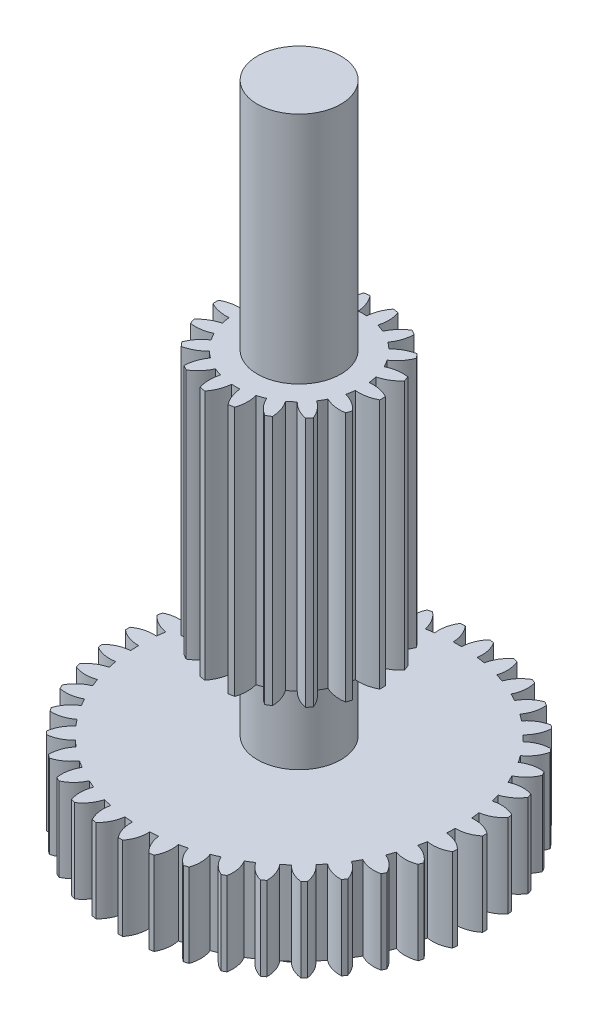
SolidWorks part; units mm, degrees
ref_plane "Front Plane" through (0, 0, 0) normal (0, 0, 1) x (1, 0, 0)
ref_plane "Top Plane" through (0, 0, 0) normal (0, 1, 0) x (1, 0, 0)
ref_plane "Right Plane" through (0, 0, 0) normal (1, 0, 0) x (0, 0, -1)
sketch "Sketch1" plane through (0, 0, 0) normal (0, 1, 0) x (1, 0, 0)
  line L0 (0, 1.896) -> (0, 2.1) construction
  arc A0 (-1.3986, 1.6198) -> (-1.4394, 1.5836) centre (0, 0) ccw
  arc A1 (-1.3323, 1.349) -> (-1.4016, 1.2769) centre (0, 0) ccw
  arc A2 (0.05, 1.8953) -> (0.145, 2.1351) centre (0.4185, 1.888) cw
  arc A3 (-0.05, 1.8953) -> (-0.145, 2.1351) centre (-0.4185, 1.888) ccw
  arc A4 (0.3534, 1.8628) -> (0.4856, 2.0842) centre (0.716, 1.7964) cw
  arc A5 (0.2547, 1.8788) -> (0.1994, 2.1307) centre (-0.1103, 1.9307) ccw
  arc A6 (0.6476, 1.782) -> (0.8136, 1.9793) centre (0.9949, 1.6583) cw
  arc A7 (0.5528, 1.8136) -> (0.5386, 2.0711) centre (0.2009, 1.9234) ccw
  arc A8 (0.9251, 1.655) -> (1.1206, 1.8231) centre (1.248, 1.4772) cw
  arc A9 (0.8365, 1.7015) -> (0.8638, 1.9579) centre (0.5068, 1.8662) ccw
  arc A10 (1.1786, 1.4852) -> (1.3986, 1.6198) centre (1.4688, 1.2579) cw
  arc A11 (1.0986, 1.5453) -> (1.1667, 1.794) centre (0.7996, 1.7608) ccw
  arc A12 (1.4016, 1.2769) -> (1.6403, 1.3744) centre (1.6516, 1.006) cw
  arc A13 (1.3323, 1.349) -> (1.4394, 1.5836) centre (1.0717, 1.6097) ccw
  arc A14 (1.5882, 1.0355) -> (1.8395, 1.0935) centre (1.7915, 0.728) cw
  arc A15 (1.5314, 1.1178) -> (1.6748, 1.3322) centre (1.316, 1.417) ccw
  arc A16 (1.7338, 0.7673) -> (1.9911, 0.7843) centre (1.8851, 0.4312) cw
  arc A17 (1.6909, 0.8577) -> (1.8668, 1.0463) centre (1.5263, 1.1875) ccw
  arc A18 (1.8344, 0.4793) -> (2.0911, 0.4547) centre (1.9299, 0.1233) cw
  arc A19 (1.8066, 0.5753) -> (2.0104, 0.7333) centre (1.697, 0.9273) ccw
  arc A20 (1.8875, 0.1788) -> (2.137, 0.1134) centre (1.9247, -0.1879) cw
  arc A21 (1.8755, 0.2781) -> (2.102, 0.4013) centre (1.8238, 0.6431) ccw
  arc A22 (1.8918, -0.1263) -> (2.1275, -0.2309) centre (1.8696, -0.4942) cw
  arc A23 (1.8958, -0.0264) -> (2.1392, 0.0589) centre (1.9033, 0.3422) ccw
  arc A24 (1.847, -0.4281) -> (2.0629, -0.5691) centre (1.7661, -0.7877) cw
  arc A25 (1.867, -0.3301) -> (2.1209, -0.285) centre (1.9336, 0.0324) ccw
  arc A26 (1.7544, -0.7188) -> (1.9449, -0.8927) centre (1.6169, -1.0608) cw
  arc A27 (1.7899, -0.6253) -> (2.0478, -0.6215) centre (1.9137, -0.2781) ccw
  arc A28 (1.6164, -0.991) -> (1.7765, -1.1931) centre (1.4258, -1.3065) cw
  arc A29 (1.6664, -0.9044) -> (1.9215, -0.942) centre (1.8443, -0.5815) ccw
  arc A30 (1.4365, -1.2374) -> (1.5621, -1.4626) centre (1.1977, -1.5183) cw
  arc A31 (1.4998, -1.16) -> (1.7455, -1.238) centre (1.7272, -0.8698) ccw
  arc A32 (1.2194, -1.4518) -> (1.3073, -1.6943) centre (0.9387, -1.6907) cw
  arc A33 (1.2943, -1.3855) -> (1.5244, -1.502) centre (1.5653, -1.1356) ccw
  arc A34 (0.9707, -1.6286) -> (1.0186, -1.882) centre (0.6553, -1.8194) cw
  arc A35 (1.0553, -1.5752) -> (1.2637, -1.7271) centre (1.3628, -1.372) ccw
  arc A36 (0.6969, -1.7633) -> (0.7035, -2.0211) centre (0.355, -1.901) cw
  arc A37 (0.7889, -1.7241) -> (0.9703, -1.9074) centre (1.1251, -1.5729) ccw
  arc A38 (0.405, -1.8522) -> (0.3702, -2.1077) centre (0.0454, -1.9333) cw
  arc A39 (0.5021, -1.8283) -> (0.6517, -2.0383) centre (0.8582, -1.733) ccw
  arc A40 (0.1027, -1.8932) -> (0.0273, -2.1398) centre (-0.2653, -1.9156) cw
  arc A41 (0.2023, -1.8852) -> (0.3163, -2.1165) centre (0.5691, -1.8482) ccw
  arc A42 (-0.2023, -1.8852) -> (-0.3163, -2.1165) centre (-0.5691, -1.8482) cw
  arc A43 (-0.1027, -1.8932) -> (-0.0273, -2.1398) centre (0.2653, -1.9156) ccw
  arc A44 (-0.5021, -1.8283) -> (-0.6517, -2.0383) centre (-0.8582, -1.733) cw
  arc A45 (-0.405, -1.8522) -> (-0.3702, -2.1077) centre (-0.0454, -1.9333) ccw
  arc A46 (-0.7889, -1.7241) -> (-0.9703, -1.9074) centre (-1.1251, -1.5729) cw
  arc A47 (-0.6969, -1.7633) -> (-0.7035, -2.0211) centre (-0.355, -1.901) ccw
  arc A48 (-1.0553, -1.5752) -> (-1.2637, -1.7271) centre (-1.3628, -1.372) cw
  arc A49 (-0.9707, -1.6286) -> (-1.0186, -1.882) centre (-0.6553, -1.8194) ccw
  arc A50 (-1.2943, -1.3855) -> (-1.5244, -1.502) centre (-1.5653, -1.1356) cw
  arc A51 (-1.2194, -1.4518) -> (-1.3073, -1.6943) centre (-0.9387, -1.6907) ccw
  arc A52 (-1.4998, -1.16) -> (-1.7455, -1.238) centre (-1.7272, -0.8698) cw
  arc A53 (-1.4365, -1.2374) -> (-1.5621, -1.4626) centre (-1.1977, -1.5183) ccw
  arc A54 (-1.6664, -0.9044) -> (-1.9215, -0.942) centre (-1.8443, -0.5815) cw
  arc A55 (-1.6164, -0.991) -> (-1.7765, -1.1931) centre (-1.4258, -1.3065) ccw
  arc A56 (-1.7899, -0.6253) -> (-2.0478, -0.6215) centre (-1.9137, -0.2781) cw
  arc A57 (-1.7544, -0.7188) -> (-1.9449, -0.8927) centre (-1.6169, -1.0608) ccw
  arc A58 (-1.867, -0.3301) -> (-2.1209, -0.285) centre (-1.9336, 0.0324) cw
  arc A59 (-1.847, -0.4281) -> (-2.0629, -0.5691) centre (-1.7661, -0.7877) ccw
  arc A60 (-1.8958, -0.0264) -> (-2.1392, 0.0589) centre (-1.9033, 0.3422) cw
  arc A61 (-1.8918, -0.1263) -> (-2.1275, -0.2309) centre (-1.8696, -0.4942) ccw
  arc A62 (-1.8755, 0.2781) -> (-2.102, 0.4013) centre (-1.8238, 0.6431) cw
  arc A63 (-1.8875, 0.1788) -> (-2.137, 0.1134) centre (-1.9247, -0.1879) ccw
  arc A64 (-1.8066, 0.5753) -> (-2.0104, 0.7333) centre (-1.697, 0.9273) cw
  arc A65 (-1.8344, 0.4793) -> (-2.0911, 0.4547) centre (-1.9299, 0.1233) ccw
  arc A66 (-1.6909, 0.8577) -> (-1.8668, 1.0463) centre (-1.5263, 1.1875) cw
  arc A67 (-1.7338, 0.7673) -> (-1.9911, 0.7843) centre (-1.8851, 0.4312) ccw
  arc A68 (-1.5314, 1.1178) -> (-1.6748, 1.3322) centre (-1.316, 1.417) cw
  arc A69 (-1.5882, 1.0355) -> (-1.8395, 1.0935) centre (-1.7915, 0.728) ccw
  arc A70 (-1.3323, 1.349) -> (-1.4394, 1.5836) centre (-1.0717, 1.6097) cw
  arc A71 (-1.4016, 1.2769) -> (-1.6403, 1.3744) centre (-1.6516, 1.006) ccw
  arc A72 (-1.0986, 1.5453) -> (-1.1667, 1.794) centre (-0.7996, 1.7608) cw
  arc A73 (-1.1786, 1.4852) -> (-1.3986, 1.6198) centre (-1.4688, 1.2579) ccw
  arc A74 (-0.8365, 1.7015) -> (-0.8638, 1.9579) centre (-0.5068, 1.8662) cw
  arc A75 (-0.9251, 1.655) -> (-1.1206, 1.8231) centre (-1.248, 1.4772) ccw
  arc A76 (-0.5528, 1.8136) -> (-0.5386, 2.0711) centre (-0.2009, 1.9234) cw
  arc A77 (-0.6476, 1.782) -> (-0.8136, 1.9793) centre (-0.9949, 1.6583) ccw
  arc A78 (-1.0986, 1.5453) -> (-1.1786, 1.4852) centre (0, 0) ccw
  arc A79 (-0.8365, 1.7015) -> (-0.9251, 1.655) centre (0, 0) ccw
  arc A80 (-0.5528, 1.8136) -> (-0.6476, 1.782) centre (0, 0) ccw
  arc A81 (0.05, 1.8953) -> (-0.05, 1.8953) centre (0, 0) ccw
  arc A82 (0.3534, 1.8628) -> (0.2547, 1.8788) centre (0, 0) ccw
  arc A83 (0.6476, 1.782) -> (0.5528, 1.8136) centre (0, 0) ccw
  arc A84 (0.9251, 1.655) -> (0.8365, 1.7015) centre (0, 0) ccw
  arc A85 (1.1786, 1.4852) -> (1.0986, 1.5453) centre (0, 0) ccw
  arc A86 (1.4016, 1.2769) -> (1.3323, 1.349) centre (0, 0) ccw
  arc A87 (1.5882, 1.0355) -> (1.5314, 1.1178) centre (0, 0) ccw
  arc A88 (1.7338, 0.7673) -> (1.6909, 0.8577) centre (0, 0) ccw
  arc A89 (1.8344, 0.4793) -> (1.8066, 0.5753) centre (0, 0) ccw
  arc A90 (1.8875, 0.1788) -> (1.8755, 0.2781) centre (0, 0) ccw
  arc A91 (1.8918, -0.1263) -> (1.8958, -0.0264) centre (0, 0) ccw
  arc A92 (1.847, -0.4281) -> (1.867, -0.3301) centre (0, 0) ccw
  arc A93 (1.7544, -0.7188) -> (1.7899, -0.6253) centre (0, 0) ccw
  arc A94 (1.6164, -0.991) -> (1.6664, -0.9044) centre (0, 0) ccw
  arc A95 (1.4365, -1.2374) -> (1.4998, -1.16) centre (0, 0) ccw
  arc A96 (1.2194, -1.4518) -> (1.2943, -1.3855) centre (0, 0) ccw
  arc A97 (0.9707, -1.6286) -> (1.0553, -1.5752) centre (0, 0) ccw
  arc A98 (0.6969, -1.7633) -> (0.7889, -1.7241) centre (0, 0) ccw
  arc A99 (0.405, -1.8522) -> (0.5021, -1.8283) centre (0, 0) ccw
  arc A100 (0.1027, -1.8932) -> (0.2023, -1.8852) centre (0, 0) ccw
  arc A101 (-0.2023, -1.8852) -> (-0.1027, -1.8932) centre (0, 0) ccw
  arc A102 (-0.5021, -1.8283) -> (-0.405, -1.8522) centre (0, 0) ccw
  arc A103 (-0.7889, -1.7241) -> (-0.6969, -1.7633) centre (0, 0) ccw
  arc A104 (-1.0553, -1.5752) -> (-0.9707, -1.6286) centre (0, 0) ccw
  arc A105 (-1.2943, -1.3855) -> (-1.2194, -1.4518) centre (0, 0) ccw
  arc A106 (-1.4998, -1.16) -> (-1.4365, -1.2374) centre (0, 0) ccw
  arc A107 (-1.6664, -0.9044) -> (-1.6164, -0.991) centre (0, 0) ccw
  arc A108 (-1.7899, -0.6253) -> (-1.7544, -0.7188) centre (0, 0) ccw
  arc A109 (-1.867, -0.3301) -> (-1.847, -0.4281) centre (0, 0) ccw
  arc A110 (-1.8958, -0.0264) -> (-1.8918, -0.1263) centre (0, 0) ccw
  arc A111 (-1.8755, 0.2781) -> (-1.8875, 0.1788) centre (0, 0) ccw
  arc A112 (-1.8066, 0.5753) -> (-1.8344, 0.4793) centre (0, 0) ccw
  arc A113 (-1.6909, 0.8577) -> (-1.7338, 0.7673) centre (0, 0) ccw
  arc A114 (-1.5314, 1.1178) -> (-1.5882, 1.0355) centre (0, 0) ccw
  arc A115 (-1.6403, 1.3744) -> (-1.6748, 1.3322) centre (0, 0) ccw
  arc A116 (-1.8395, 1.0935) -> (-1.8668, 1.0463) centre (0, 0) ccw
  arc A117 (-1.9911, 0.7843) -> (-2.0104, 0.7333) centre (0, 0) ccw
  arc A118 (-1.1206, 1.8231) -> (-1.1667, 1.794) centre (0, 0) ccw
  arc A119 (-0.8136, 1.9793) -> (-0.8638, 1.9579) centre (0, 0) ccw
  arc A120 (-0.145, 2.1351) -> (-0.1994, 2.1307) centre (0, 0) ccw
  arc A121 (0.1994, 2.1307) -> (0.145, 2.1351) centre (0, 0) ccw
  arc A122 (0.5386, 2.0711) -> (0.4856, 2.0842) centre (0, 0) ccw
  arc A123 (0.8638, 1.9579) -> (0.8136, 1.9793) centre (0, 0) ccw
  arc A124 (1.1667, 1.794) -> (1.1206, 1.8231) centre (0, 0) ccw
  arc A125 (1.4394, 1.5836) -> (1.3986, 1.6198) centre (0, 0) ccw
  arc A126 (1.6748, 1.3322) -> (1.6403, 1.3744) centre (0, 0) ccw
  arc A127 (1.8668, 1.0463) -> (1.8395, 1.0935) centre (0, 0) ccw
  arc A128 (2.0104, 0.7333) -> (1.9911, 0.7843) centre (0, 0) ccw
  arc A129 (2.102, 0.4013) -> (2.0911, 0.4547) centre (0, 0) ccw
  arc A130 (2.1392, 0.0589) -> (2.137, 0.1134) centre (0, 0) ccw
  arc A131 (2.1209, -0.285) -> (2.1275, -0.2309) centre (0, 0) ccw
  arc A132 (2.0478, -0.6215) -> (2.0629, -0.5691) centre (0, 0) ccw
  arc A133 (1.9215, -0.942) -> (1.9449, -0.8927) centre (0, 0) ccw
  arc A134 (1.7455, -1.238) -> (1.7765, -1.1931) centre (0, 0) ccw
  arc A135 (1.5244, -1.502) -> (1.5621, -1.4626) centre (0, 0) ccw
  arc A136 (1.2637, -1.7271) -> (1.3073, -1.6943) centre (0, 0) ccw
  arc A137 (0.9703, -1.9074) -> (1.0186, -1.882) centre (0, 0) ccw
  arc A138 (0.6517, -2.0383) -> (0.7035, -2.0211) centre (0, 0) ccw
  arc A139 (0.3163, -2.1165) -> (0.3702, -2.1077) centre (0, 0) ccw
  arc A140 (-0.0273, -2.1398) -> (0.0273, -2.1398) centre (0, 0) ccw
  arc A141 (-0.3702, -2.1077) -> (-0.3163, -2.1165) centre (0, 0) ccw
  arc A142 (-0.7035, -2.0211) -> (-0.6517, -2.0383) centre (0, 0) ccw
  arc A143 (-1.0186, -1.882) -> (-0.9703, -1.9074) centre (0, 0) ccw
  arc A144 (-1.3073, -1.6943) -> (-1.2637, -1.7271) centre (0, 0) ccw
  arc A145 (-1.5621, -1.4626) -> (-1.5244, -1.502) centre (0, 0) ccw
  arc A146 (-1.7765, -1.1931) -> (-1.7455, -1.238) centre (0, 0) ccw
  arc A147 (-1.9449, -0.8927) -> (-1.9215, -0.942) centre (0, 0) ccw
  arc A148 (-2.0629, -0.5691) -> (-2.0478, -0.6215) centre (0, 0) ccw
  arc A149 (-2.1275, -0.2309) -> (-2.1209, -0.285) centre (0, 0) ccw
  arc A150 (-2.137, 0.1134) -> (-2.1392, 0.0589) centre (0, 0) ccw
  arc A151 (-2.0911, 0.4547) -> (-2.102, 0.4013) centre (0, 0) ccw
  arc A152 (-0.2547, 1.8788) -> (-0.1994, 2.1307) centre (0.1103, 1.9307) cw
  arc A153 (-0.3534, 1.8628) -> (-0.4856, 2.0842) centre (-0.716, 1.7964) ccw
  arc A154 (-0.4856, 2.0842) -> (-0.5386, 2.0711) centre (0, 0) ccw
  arc A155 (-0.3534, 1.8628) -> (-0.2547, 1.8788) centre (0, 0) cw
  point P4 (0, 2.14)
  point P5 (0, 1.896)
  point P237 (0, 0)
  dimension "D1" = 4.28
  dimension "D3" = 0.145
  dimension "D2" = 0.244
  dimension "D4" = 0.05
  dimension "D5" = 39
extrude "Boss-Extrude1" add sketch "Sketch1" along normal blind 1
sketch "Sketch2" plane through (0, 1, 0) normal (0, 1, 0) x (1, 0, 0)
  circle A0 centre (0, 0) radius 0.5
  dimension "D1" = 1
extrude "Boss-Extrude2" add sketch "Sketch2" along normal blind 6.8 and the other way blind 2
ref_plane "Plane1" through (0, 2, 0) normal (0, 1, 0) x (1, 0, 0)
sketch "Sketch3" plane through (0, 2, 0) normal (0, 1, 0) x (1, 0, 0)
  circle A0 centre (0, 0) radius 1
  dimension "D1" = 2
extrude "Boss-Extrude3" add sketch "Sketch3" along normal blind 3
sketch "Sketch4" plane through (0, 5, 0) normal (0, 1, 0) x (1, 0, 0)
  line L0 (0, 1) -> (0, 1.2075) construction
  arc A0 (-0.6318, 0.4225) -> (-0.6818, 0.3359) centre (0, 0) ccw
  circle A1 centre (0, 0) radius 1 construction
  arc A2 (0.05, 0.7584) -> (0.14, 0.9902) centre (0.4695, 0.7288) cw
  arc A3 (-0.05, 0.7584) -> (-0.14, 0.9902) centre (-0.4695, 0.7288) ccw
  arc A4 (0.3064, 0.6955) -> (0.4702, 0.8826) centre (0.6905, 0.5243) cw
  arc A5 (0.2124, 0.7297) -> (0.2071, 0.9783) centre (-0.1919, 0.8455) ccw
  arc A6 (0.5258, 0.5488) -> (0.7437, 0.6685) centre (0.8282, 0.2565) cw
  arc A7 (0.4492, 0.6131) -> (0.5292, 0.8485) centre (0.1088, 0.8601) ccw
  arc A8 (0.6818, 0.3359) -> (0.9275, 0.3738) centre (0.866, -0.0422) cw
  arc A9 (0.6318, 0.4225) -> (0.7875, 0.6163) centre (0.3964, 0.771) ccw
  arc A10 (0.7555, 0.0824) -> (0.9994, 0.0341) centre (0.7993, -0.3358) cw
  arc A11 (0.7381, 0.1809) -> (0.9508, 0.3098) centre (0.6362, 0.589) ccw
  arc A12 (0.7381, -0.1809) -> (0.9508, -0.3098) centre (0.6362, -0.589) cw
  arc A13 (0.7555, -0.0824) -> (0.9994, -0.0341) centre (0.7993, 0.3358) ccw
  arc A14 (0.6318, -0.4225) -> (0.7875, -0.6163) centre (0.3964, -0.771) cw
  arc A15 (0.6818, -0.3359) -> (0.9275, -0.3738) centre (0.866, 0.0422) ccw
  arc A16 (0.4492, -0.6131) -> (0.5292, -0.8485) centre (0.1088, -0.8601) cw
  arc A17 (0.5258, -0.5488) -> (0.7437, -0.6685) centre (0.8282, -0.2565) ccw
  arc A18 (0.2124, -0.7297) -> (0.2071, -0.9783) centre (-0.1919, -0.8455) cw
  arc A19 (0.3064, -0.6955) -> (0.4702, -0.8826) centre (0.6905, -0.5243) ccw
  arc A20 (-0.05, -0.7584) -> (-0.14, -0.9902) centre (-0.4695, -0.7288) cw
  arc A21 (0.05, -0.7584) -> (0.14, -0.9902) centre (0.4695, -0.7288) ccw
  arc A22 (-0.3064, -0.6955) -> (-0.4702, -0.8826) centre (-0.6905, -0.5243) cw
  arc A23 (-0.2124, -0.7297) -> (-0.2071, -0.9783) centre (0.1919, -0.8455) ccw
  arc A24 (-0.5258, -0.5488) -> (-0.7437, -0.6685) centre (-0.8282, -0.2565) cw
  arc A25 (-0.4492, -0.6131) -> (-0.5292, -0.8485) centre (-0.1088, -0.8601) ccw
  arc A26 (-0.6818, -0.3359) -> (-0.9275, -0.3738) centre (-0.866, 0.0422) cw
  arc A27 (-0.6318, -0.4225) -> (-0.7875, -0.6163) centre (-0.3964, -0.771) ccw
  arc A28 (-0.7555, -0.0824) -> (-0.9994, -0.0341) centre (-0.7993, 0.3358) cw
  arc A29 (-0.7381, -0.1809) -> (-0.9508, -0.3098) centre (-0.6362, -0.589) ccw
  arc A30 (-0.7381, 0.1809) -> (-0.9508, 0.3098) centre (-0.6362, 0.589) cw
  arc A31 (-0.7555, 0.0824) -> (-0.9994, 0.0341) centre (-0.7993, -0.3358) ccw
  arc A32 (-0.6318, 0.4225) -> (-0.7875, 0.6163) centre (-0.3964, 0.771) cw
  arc A33 (-0.6818, 0.3359) -> (-0.9275, 0.3738) centre (-0.866, -0.0422) ccw
  arc A34 (-0.4492, 0.6131) -> (-0.5292, 0.8485) centre (-0.1088, 0.8601) cw
  arc A35 (-0.5258, 0.5488) -> (-0.7437, 0.6685) centre (-0.8282, 0.2565) ccw
  arc A36 (-0.2124, 0.7297) -> (-0.2071, 0.9783) centre (0.1919, 0.8455) cw
  arc A37 (-0.3064, 0.6955) -> (-0.4702, 0.8826) centre (-0.6905, 0.5243) ccw
  arc A38 (-0.9994, 0.0341) -> (-0.9994, -0.0341) centre (0, 0) ccw
  arc A39 (-0.7381, 0.1809) -> (-0.7555, 0.0824) centre (0, 0) ccw
  arc A40 (-0.7555, -0.0824) -> (-0.7381, -0.1809) centre (0, 0) ccw
  arc A41 (-0.6818, -0.3359) -> (-0.6318, -0.4225) centre (0, 0) ccw
  arc A42 (-0.5258, -0.5488) -> (-0.4492, -0.6131) centre (0, 0) ccw
  arc A43 (-0.3064, -0.6955) -> (-0.2124, -0.7297) centre (0, 0) ccw
  arc A44 (-0.05, -0.7584) -> (0.05, -0.7584) centre (0, 0) ccw
  arc A45 (0.2124, -0.7297) -> (0.3064, -0.6955) centre (0, 0) ccw
  arc A46 (0.4492, -0.6131) -> (0.5258, -0.5488) centre (0, 0) ccw
  arc A47 (0.6318, -0.4225) -> (0.6818, -0.3359) centre (0, 0) ccw
  arc A48 (0.7381, -0.1809) -> (0.7555, -0.0824) centre (0, 0) ccw
  arc A49 (0.7555, 0.0824) -> (0.7381, 0.1809) centre (0, 0) ccw
  arc A50 (0.6818, 0.3359) -> (0.6318, 0.4225) centre (0, 0) ccw
  arc A51 (0.5258, 0.5488) -> (0.4492, 0.6131) centre (0, 0) ccw
  arc A52 (0.3064, 0.6955) -> (0.2124, 0.7297) centre (0, 0) ccw
  arc A53 (0.05, 0.7584) -> (-0.05, 0.7584) centre (0, 0) ccw
  arc A54 (-0.2124, 0.7297) -> (-0.3064, 0.6955) centre (0, 0) ccw
  arc A55 (-0.4492, 0.6131) -> (-0.5258, 0.5488) centre (0, 0) ccw
  arc A56 (-0.9508, -0.3098) -> (-0.9275, -0.3738) centre (0, 0) ccw
  arc A57 (-0.7875, -0.6163) -> (-0.7437, -0.6685) centre (0, 0) ccw
  arc A58 (-0.5292, -0.8485) -> (-0.4702, -0.8826) centre (0, 0) ccw
  arc A59 (-0.2071, -0.9783) -> (-0.14, -0.9902) centre (0, 0) ccw
  arc A60 (0.14, -0.9902) -> (0.2071, -0.9783) centre (0, 0) ccw
  arc A61 (0.4702, -0.8826) -> (0.5292, -0.8485) centre (0, 0) ccw
  arc A62 (0.7437, -0.6685) -> (0.7875, -0.6163) centre (0, 0) ccw
  arc A63 (0.9275, -0.3738) -> (0.9508, -0.3098) centre (0, 0) ccw
  arc A64 (0.9994, -0.0341) -> (0.9994, 0.0341) centre (0, 0) ccw
  arc A65 (0.9508, 0.3098) -> (0.9275, 0.3738) centre (0, 0) ccw
  arc A66 (0.7875, 0.6163) -> (0.7437, 0.6685) centre (0, 0) ccw
  arc A67 (0.5292, 0.8485) -> (0.4702, 0.8826) centre (0, 0) ccw
  arc A68 (0.2071, 0.9783) -> (0.14, 0.9902) centre (0, 0) ccw
  arc A69 (-0.14, 0.9902) -> (-0.2071, 0.9783) centre (0, 0) ccw
  arc A70 (-0.9275, 0.3738) -> (-0.9508, 0.3098) centre (0, 0) ccw
  arc A71 (-0.7437, 0.6685) -> (-0.7875, 0.6163) centre (0, 0) ccw
  arc A72 (-0.4702, 0.8826) -> (-0.5292, 0.8485) centre (0, 0) ccw
  point P3 (0, 1)
  point P4 (0, 0.76)
  point P119 (0, 0)
  dimension "D1" = 0.24
  dimension "D2" = 0.05
  dimension "D3" = 0.14
  dimension "D4" = 18
extrude "Cut-Extrude1" cut sketch "Sketch4" against normal blind 3 flip side to cut contours A43 A23 A59 A20 A44 A21 A60 A18 A45 A19 A61 A16 A46 A17 A62 A14 A47 A15 A63 A12 A48 A13 A64 A10 A49 A11 A65 A8 A50 A9 A66 A6 A51 A7 A67 A4 A52 A5 A68 A2 A53 A3 A69 A36 A54 A37 A72 A34 A55 A35 A71 A32 A0 A33 A70 A30 A39 A31 A38 A28 A40 A29 A56 A26 A41 A27 A57 A24 A42 A25 A58 A22
